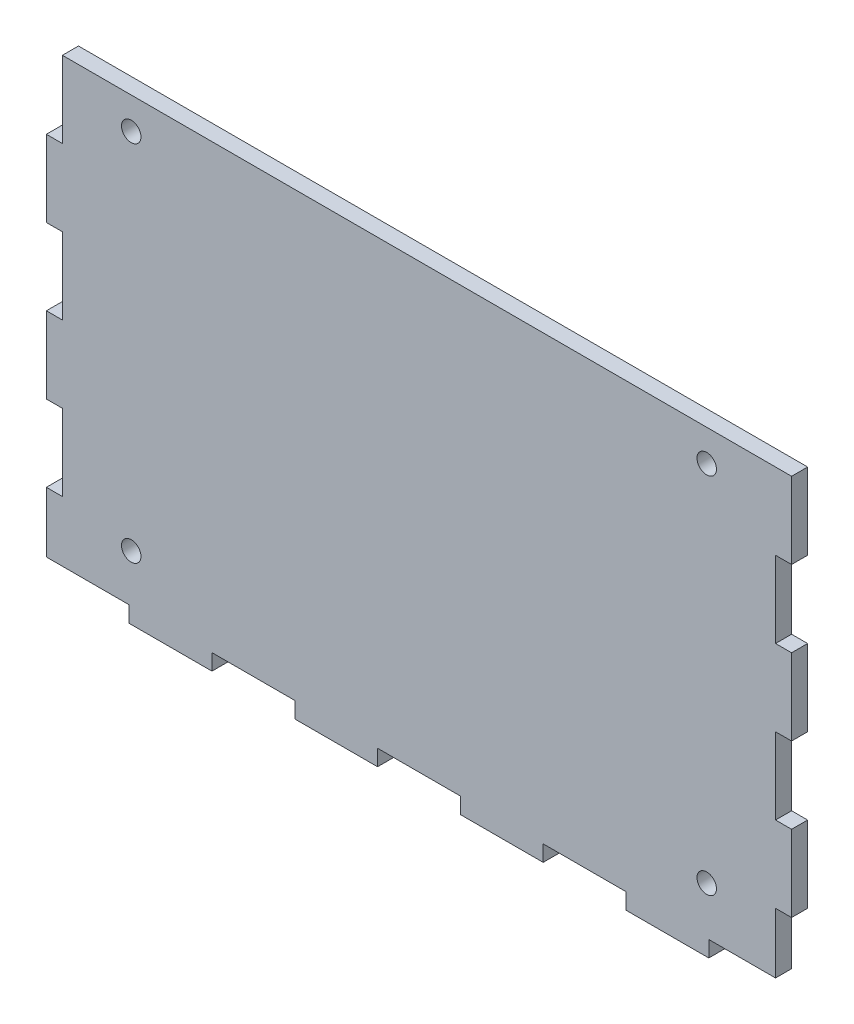
SolidWorks part; units mm, degrees
material "Acrylic (Medium-high impact)"
ref_plane "Front Plane" through (0, 0, 0) normal (0, 0, 1) x (1, 0, 0)
ref_plane "Top Plane" through (0, 0, 0) normal (0, 1, 0) x (1, 0, 0)
ref_plane "Right Plane" through (0, 0, 0) normal (1, 0, 0) x (0, 0, -1)
sketch "Sketch1" plane through (0, 0, 0) normal (0, 0, 1) x (1, 0, 0)
  line L1 (0, 0) -> (130, 0)
  line L2 (0, 0) -> (0, 80)
  line L3 (0, 80) -> (130, 80)
  line L4 (130, 0) -> (130, 80)
  dimension "D1" = 130
  dimension "D2" = 80
extrude "Boss-Extrude1" add sketch "Sketch1" along normal blind 2.8
sketch "Sketch2" plane through (0, 0, 2.8) normal (0, 0, 1) x (1, 0, 0)
  line L61 (14.4444, 2.8) -> (28.8889, 2.8) construction
  line L62 (0, 0) -> (14.4444, 0)
  line L67 (0, 0) -> (0, 2.8)
  line L72 (0, 2.8) -> (14.4444, 2.8)
  line L77 (14.4444, 0) -> (14.4444, 2.8)
  line L97 (28.8889, 0) -> (28.8889, 2.8)
  line L98 (28.8889, 0) -> (43.3333, 0)
  line L107 (43.3333, 0) -> (43.3333, 2.8)
  line L115 (28.8889, 2.8) -> (43.3333, 2.8)
  line L117 (43.3333, 2.8) -> (57.7778, 2.8) construction
  line L123 (57.7778, 0) -> (57.7778, 2.8)
  line L128 (57.7778, 0) -> (72.2222, 0)
  line L129 (72.2222, 0) -> (72.2222, 2.8)
  line L131 (57.7778, 2.8) -> (72.2222, 2.8)
  line L132 (72.2222, 2.8) -> (86.6667, 2.8) construction
  line L133 (86.6667, 0) -> (86.6667, 2.8)
  line L134 (86.6667, 0) -> (101.1111, 0)
  line L135 (101.1111, 0) -> (101.1111, 2.8)
  line L136 (86.6667, 2.8) -> (101.1111, 2.8)
  line L137 (101.1111, 2.8) -> (115.5556, 2.8) construction
  line L138 (115.5556, 0) -> (115.5556, 2.8)
  line L139 (115.5556, 0) -> (130, 0)
  line L142 (130, 0) -> (130, 80) construction
  line L143 (0, 80) -> (0, 0) construction
  line L144 (0, 13.3333) -> (2.8, 13.3333)
  line L145 (0, 13.3333) -> (0, 26.6667)
  line L146 (130, 2.8) -> (144.4444, 2.8) construction
  line L147 (0, 26.6667) -> (2.8, 26.6667)
  line L148 (2.8, 13.3333) -> (2.8, 26.6667)
  line L149 (2.8, 13.3333) -> (2.8, 0) construction
  line L150 (0, 40) -> (0, 53.3333)
  line L151 (0, 40) -> (2.8, 40)
  line L152 (2.8, 40) -> (2.8, 53.3333)
  line L153 (0, 53.3333) -> (2.8, 53.3333)
  line L154 (2.8, 40) -> (2.8, 26.6667) construction
  line L155 (0, 66.6667) -> (0, 80)
  line L156 (0, 66.6667) -> (2.8, 66.6667)
  line L157 (2.8, 66.6667) -> (2.8, 80)
  line L158 (0, 80) -> (2.8, 80)
  line L159 (2.8, 66.6667) -> (2.8, 53.3333) construction
  line L160 (130, 80) -> (0, 80) construction
  line L161 (127.2, 80) -> (127.2, 66.6667) construction
  line L162 (127.2, 40) -> (127.2, 26.6667)
  line L163 (127.2, 66.6667) -> (130, 66.6667)
  line L164 (127.2, 66.6667) -> (127.2, 53.3333)
  line L165 (127.2, 53.3333) -> (130, 53.3333)
  line L166 (130, 66.6667) -> (130, 53.3333)
  line L167 (127.2, 40) -> (130, 40)
  line L168 (130, 40) -> (130, 26.6667)
  line L169 (127.2, 26.6667) -> (130, 26.6667)
  line L170 (127.2, 53.3333) -> (127.2, 40) construction
  line L172 (127.2, 13.3333) -> (130, 13.3333)
  line L173 (130, 13.3333) -> (130, 0)
  line L175 (127.2, 26.6667) -> (127.2, 13.3333) construction
  line L183 (115.5556, 2.8) -> (130, 2.8) [skipped]
  line L184 (130, 0) -> (130, 2.8) [skipped]
  line L185 (127.2, 13.3333) -> (127.2, 2.8)
  line L186 (127.2, 2.8) -> (115.5556, 2.8)
  line L187 (127.2, 0) -> (130, 0) [skipped]
  line L188 (127.2, 13.3333) -> (127.2, 0) [skipped]
  dimension "D2" = 2.8
  dimension "D4" = 2.8
  dimension "D6" = 2.8
  dimension "D1" = 5
  dimension "D3" = 3
  dimension "D5" = 3
extrude "Cut-Extrude1" cut sketch "Sketch2" against normal through all
sketch "Sketch3" plane through (0, 0, 2.8) normal (0, 0, 1) x (1, 0, 0)
  line L0 (0, 66.6667) -> (0, 53.3333) construction
  line L1 (130, 80) -> (2.8, 80) construction
  line L2 (0, 66.6667) -> (130, 66.6667) construction
  line L3 (65, 66.6667) -> (65, 50066.6667) construction
  line L4 (14.4444, 2.8) -> (0, 2.8) construction
  line L5 (14.8, 74.5) -> (115.2, 74.5) construction
  line L6 (14.8, 74.5) -> (14.8, 11.1248) construction
  line L7 (14.8, 11.1248) -> (115.2, 11.1248) construction
  line L8 (115.2, 74.5) -> (115.2, 11.1248) construction
  circle A0 centre (14.8, 74.5) radius 1.7
  circle A1 centre (115.2, 74.5) radius 1.7
  circle A2 centre (14.8, 11.1248) radius 1.7
  circle A3 centre (115.2, 11.1248) radius 1.7
  point P10 (65, 66.6667)
  point P19 (14.8, 14.3265)
  point P23 (115.6794, 74.5)
  dimension "D1" = 3.4
  dimension "D2" = 14.8
  dimension "D3" = 5.5
  dimension "D4" = 8.3248
extrude "Cut-Extrude2" cut sketch "Sketch3" against normal up to next
other "Width tolerance" face at (128.6, 53.3333, 1.4) face at (128.6, 26.6667, 1.4) face at (128.6, 13.3333, 1.4) face at (128.6, 40, 1.4) face at (128.6, 66.6667, 1.4) face at (115.5556, 1.4, 1.4) face at (86.6667, 1.4, 1.4) face at (57.7778, 1.4, 1.4) face at (28.8889, 1.4, 1.4) face at (14.4444, 1.4, 1.4) face at (43.3333, 1.4, 1.4) face at (72.2222, 1.4, 1.4) face at (101.1111, 1.4, 1.4) face at (1.4, 26.6667, 1.4) face at (1.4, 13.3333, 1.4) face at (1.4, 40, 1.4) face at (1.4, 53.3333, 1.4) face at (1.4, 66.6667, 1.4) parameters "D1"=0
equation "\"wall_thickness\"= 2.8mm"
equation "\"D1@Boss-Extrude1\"=\"wall_thickness\""
equation "\"slot_width_tolerance\"= 0.0mm"
equation "\"slot_depth\"= 2.8mm"
equation "\"D2@Sketch2\"=\"slot_depth\""
equation "\"D4@Sketch2\"=\"slot_depth\""
equation "\"D6@Sketch2\"=\"slot_depth\""
equation "\"D2@Sketch3\"=12.00mm+\"slot_depth\""
equation "\"D1@Width tolerance\" = \"slot_width_tolerance\""
